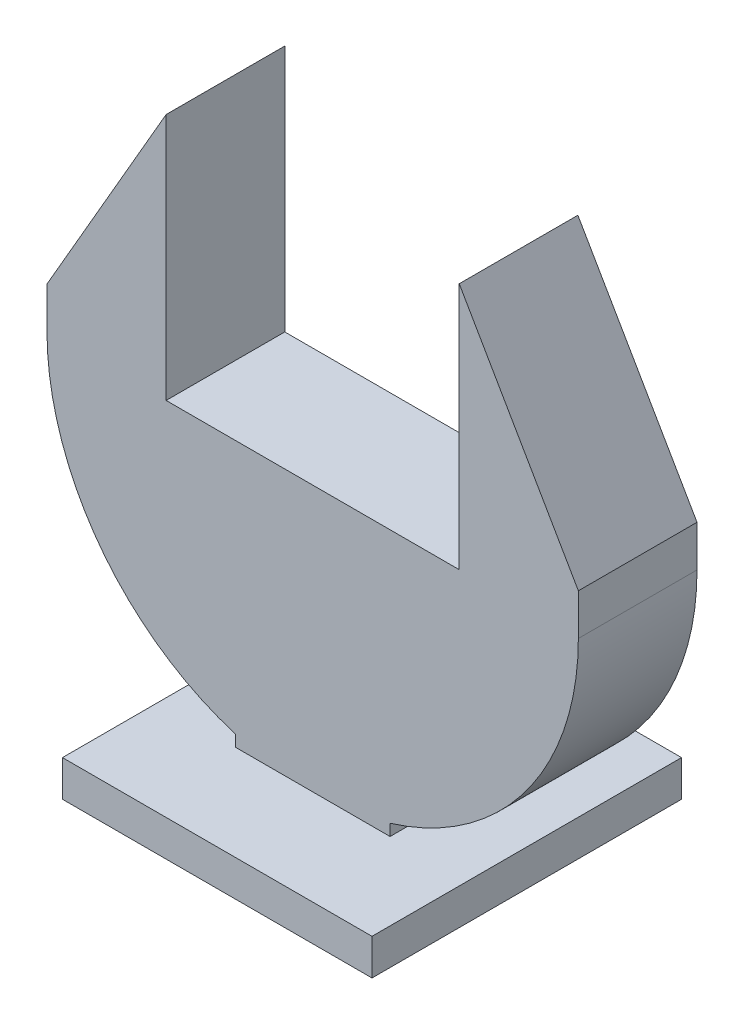
SolidWorks part; units mm, degrees
ref_plane "前视基准面" through (0, 0, 0) normal (0, 0, 1) x (1, 0, 0)
ref_plane "上视基准面" through (0, 0, 0) normal (0, 1, 0) x (1, 0, 0)
ref_plane "右视基准面" through (0, 0, 0) normal (1, 0, 0) x (0, 0, -1)
other "Configuration Table"
sketch "草图2" plane through (0, 0, 0) normal (0, 1, 0) x (1, 0, 0)
  line L1 (-30, -30) -> (30, -30)
  line L2 (-30, -30) -> (-30, 30)
  line L3 (-30, 30) -> (30, 30)
  line L4 (30, -30) -> (30, 30)
  line L5 (-30, -30) -> (30, 30) construction
  line L6 (-30, 30) -> (30, -30) construction
  point P0 (0, 0)
  dimension "D1" = 60
  dimension "D2" = 60
extrude "凸台-拉伸1" add sketch "草图2" along normal blind 7
sketch "草图3" plane through (0, 0, 0) normal (0, 0, 1) x (1, 0, 0)
  line L0 (-30, 7) -> (30, 7) construction
  line L1 (-28.406, 58.5) -> (28.406, 58.5)
  line L2 (0, -1000) -> (0, 49000) construction
  line L3 (-51.5, 58.5) -> (-51.5, 66.5)
  line L4 (-51.5, 66.5) -> (-28.406, 106.5)
  line L5 (-28.406, 106.5) -> (-28.406, 66.5)
  line L6 (-28.406, 66.5) -> (-28.406, 58.5)
  line L7 (-28.406, 66.5) -> (-51.5, 66.5) construction
  line L8 (51.5, 66.5) -> (28.406, 106.5)
  line L9 (51.5, 58.5) -> (51.5, 66.5)
  line L10 (28.406, 66.5) -> (28.406, 58.5)
  line L11 (28.406, 106.5) -> (28.406, 66.5)
  line L12 (-30, 0) -> (30, 0) construction
  line L13 (15, 7) -> (15, 9.2329)
  line L14 (-15, 7) -> (-15, 9.2329)
  line L15 (-15, 7) -> (15, 7)
  arc A0 (-51.5, 58.5) -> (-15, 9.2329) centre (0, 58.5) ccw
  arc A1 (15, 9.2329) -> (51.5, 58.5) centre (0, 58.5) ccw
  dimension "D1" = 103
  dimension "D2" = 8
  dimension "D3" = 40
  dimension "D4" = 60
  dimension "D5" = 58.5
  dimension "D6" = 15
  dimension "D7" = 15
extrude "凸台-拉伸2" add sketch "草图3" along normal blind 11.5 and the other way blind 11.5
